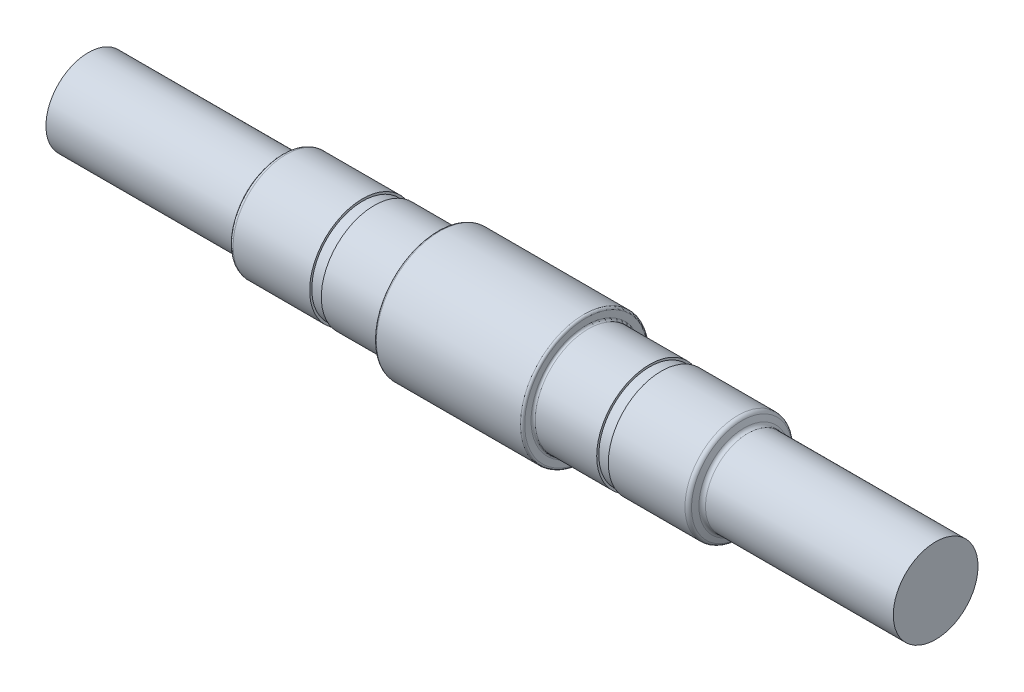
SolidWorks part; units mm, degrees
material "Plain Carbon Steel"
ref_plane "Front" through (0, 0, 0) normal (0, 0, 1) x (1, 0, 0)
ref_plane "Top" through (0, 0, 0) normal (0, 1, 0) x (1, 0, 0)
ref_plane "Right" through (0, 0, 0) normal (1, 0, 0) x (0, 0, -1)
sketch "Sketch1" plane through (0, 0, 0) normal (1, 0, 0) x (0, 0, -1)
  circle A0 centre (0, 0) radius 4
  dimension "D1" = 8
extrude "Boss-Extrude1" add sketch "Sketch1" along normal blind 40
cosmetic thread "Cosmetic Thread1" parameters "D1"=8, "D2"=7
sketch "Sketch2" plane through (0, 0, 0) normal (1, 0, 0) x (0, 0, -1)
  circle A0 centre (0, 0) radius 6
  dimension "D1" = 12
extrude "Boss-Extrude2" add sketch "Sketch2" along normal blind 7
sketch "Sketch3" plane through (0, 0, 0) normal (1, 0, 0) x (0, 0, -1)
  circle A0 centre (0, 0) radius 5
  dimension "D1" = 10
extrude "Boss-Extrude3" add sketch "Sketch3" along normal blind 21.6
fillet "Fillet1" radius 0.2 2 edges at (7, 0, -6) (7, 0, -5)
ref_plane "Plane1" through (13, 0, 0) normal (1, 0, 0) x (0, 0, -1)
sketch "Sketch4" plane through (13, 0, 0) normal (1, 0, 0) x (0, 0, -1)
  circle A0 centre (0, 0) radius 4.8
  circle A1 centre (0, 0) radius 8.0777
  dimension "D1" = 9.6
extrude "Cut-Extrude1" cut sketch "Sketch4" along normal blind 1.1
sketch "Sketch5" plane through (0, 0, 0) normal (0, 0, 1) x (1, 0, 0)
  line L0 (21.6, 5) -> (21.6, 4)
  line L1 (21.6, 4) -> (22.004, 4)
  line L2 (40, 4) -> (21.6, 4) construction
  line L3 (22.004, 4) -> (21.6, 5)
  dimension "D1" = 68
ref_axis "Axis1" through (21.6, 0, 0) along (-1, 0, 0)
revolve "Revolve1" add sketch "Sketch5" angle 360 about axis through (21.6, 0, 0) along (-1, 0, 0)
fillet "Fillet3" radius 0.4 2 edges at (22.004, 0, -4) (21.6, 0, -5)
mirror "Mirror1" about plane through (0, 0, 0) normal (1, 0, 0) of "Revolve1", "Fillet1", "Boss-Extrude3", "Boss-Extrude1", "Boss-Extrude2", "Cut-Extrude1", "Fillet3"
